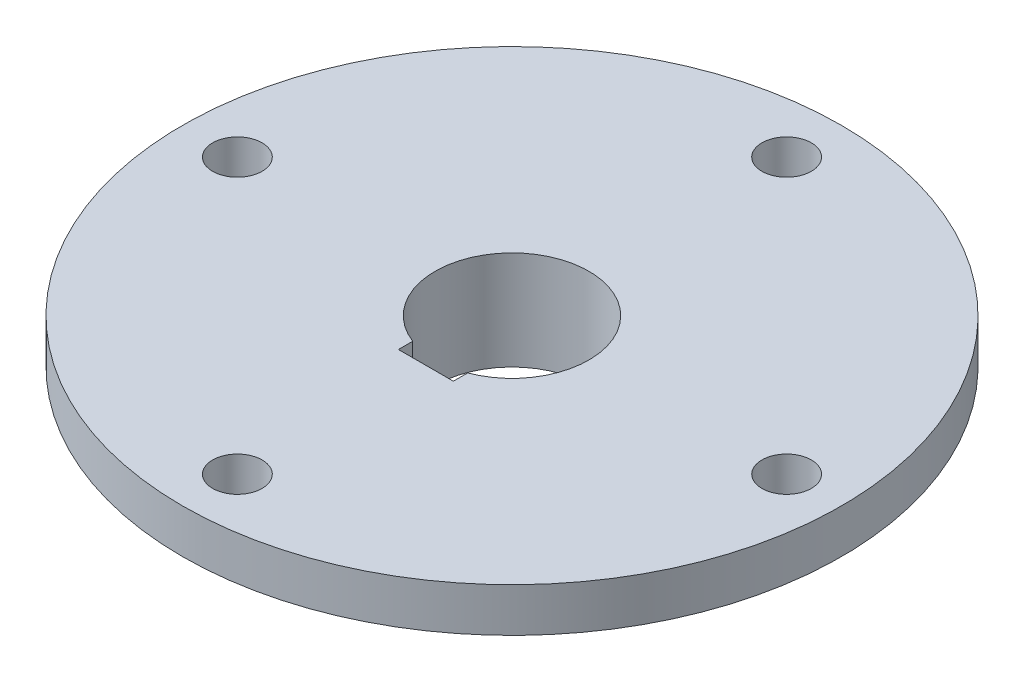
SolidWorks part; units mm, degrees
material "1.0037 (S235JR)"
ref_plane "Ebene vorne" through (0, 0, 0) normal (0, 0, 1) x (1, 0, 0)
ref_plane "Ebene oben" through (0, 0, 0) normal (0, 1, 0) x (1, 0, 0)
ref_plane "Ebene rechts" through (0, 0, 0) normal (1, 0, 0) x (0, 0, -1)
sketch "Skizze1" plane through (0, 0, 0) normal (0, 1, 0) x (1, 0, 0)
  circle A0 centre (0, 0) radius 7
  circle A1 centre (0, 0) radius 20.5
  dimension "D1" = 14
  dimension "D2" = 41
extrude "Aufsatz-Linear austragen1" add sketch "Skizze1" along normal blind 5
sketch "Skizze3" plane through (0, 5, 0) normal (0, 1, 0) x (1, 0, 0)
  circle A1 centre (0, 0) radius 30
  circle A2 centre (0, 0) radius 7 construction
  circle A3 centre (0, 0) radius 7
  dimension "D1" = 60
extrude "Aufsatz-Linear austragen2" add sketch "Skizze3" along normal blind 4
hole_wizard "Durchgangsloch für M41" positions "Skizze4" profile "Skizze5" hole size "M4" standard "ANSI Metrisch" end condition through all
sketch "Skizze4" plane through (0, 5, 0) normal (0, -1, 0) x (-1, 0, 0)
  circle A0 centre (0, 0) radius 25 construction
  point P0 (0, 25)
  point P8 (-25, 0)
  point P10 (0, -25)
  point P12 (25, 0)
  dimension "D1" = 50
sketch "Skizze5" plane through (0, 5, -25) normal (1, 0, 0) x (0, 0, -1)
  line L0 (0, 0) -> (0, 4)
  line L1 (0, 4) -> (2.25, 4)
  line L2 (2.25, 4) -> (2.25, 0)
  line L5 (2.25, 0) -> (0, 0)
  line L11 (0, -6.35) -> (0, 107.95) construction
  dimension "Bohrerdurchmesser" = 4.5
  dimension "Bohrungstiefe" = 4
sketch "Skizze6" plane through (0, 0, 0) normal (0, -1, 0) x (1, 0, 0)
  line L0 (2.5, 7.8383) -> (-2.5, 7.8383)
  line L1 (0, -4.95) -> (0, 4.95) construction
  line L2 (-2.5, 7.8383) -> (-2.5, 6.5383)
  line L3 (2.5, 7.8383) -> (2.5, 6.5383)
  circle A0 centre (0, 0) radius 7 construction
  arc A1 (2.5, 6.5383) -> (-2.5, 6.5383) centre (0, 0) ccw
  point P10 (0, 7.8383)
  dimension "D1" = 2.5
  dimension "D2" = 1.3
extrude "Schnitt-Linear austragen1" cut sketch "Skizze6" against normal through all both and the other way through all
